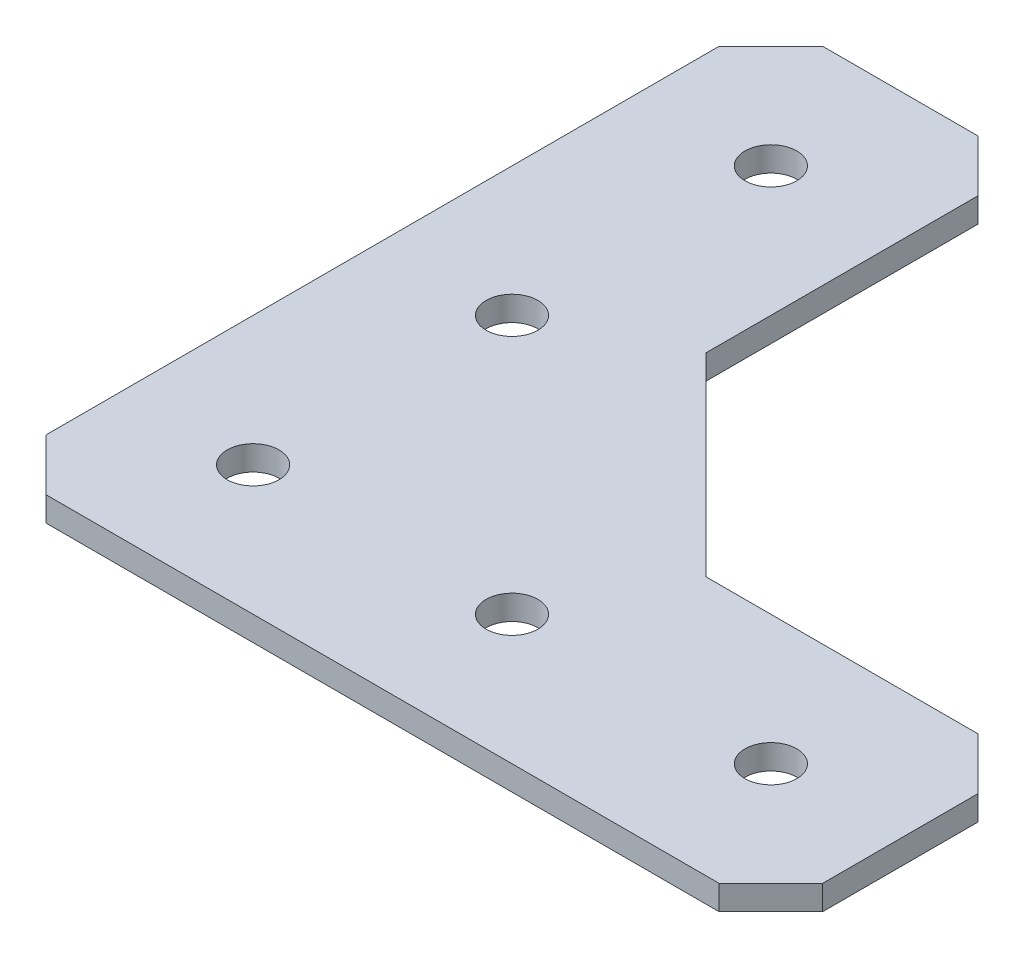
SolidWorks part; units mm, degrees
ref_plane "Front Plane" through (0, 0, 0) normal (0, 0, 1) x (1, 0, 0)
ref_plane "Top Plane" through (0, 0, 0) normal (0, 1, 0) x (1, 0, 0)
ref_plane "Right Plane" through (0, 0, 0) normal (1, 0, 0) x (0, 0, -1)
sketch "Sketch1" plane through (0, 0, 0) normal (0, 1, 0) x (1, 0, 0)
  line L0 (25.4, 76.2) -> (25.4, 25.4)
  line L1 (0, 0) -> (76.2, 0)
  line L2 (0, 0) -> (0, 76.2)
  line L3 (0, 76.2) -> (25.4, 76.2)
  line L4 (76.2, 0) -> (76.2, 25.4)
  line L5 (25.4, 25.4) -> (76.2, 25.4)
  point P1 (25.4, 23.2833)
  point P7 (25.4, 25.4)
  dimension "D1" = 25.4
  dimension "D2" = 76.2
extrude "Boss-Extrude1" add sketch "Sketch1" along normal blind 2.413
chamfer "Chamfer1" distance 19.05 angle 45 1 edges at (25.4, 1.2065, -25.4)
chamfer "Chamfer2" distance 5.08 angle 45 5 edges at (0, 1.2065, -76.2) (25.4, 1.2065, -76.2) (76.2, 1.2065, -25.4) (76.2, 1.2065, 0) (0, 1.2065, 0)
sketch "Sketch2" plane through (0, 0, 0) normal (0, 1, 0) x (1, 0, 0)
  line L0 (12.7, 76.2) -> (12.7, 0) construction
  line L1 (20.32, 76.2) -> (5.08, 76.2) construction
  line L2 (5.08, 0) -> (71.12, 0) construction
  line L3 (76.2, 12.7) -> (0, 12.7) construction
  line L4 (76.2, 5.08) -> (76.2, 20.32) construction
  line L5 (0, 71.12) -> (0, 5.08) construction
  circle A0 centre (12.7, 12.7) radius 2.54
  circle A1 centre (12.7, 38.1) radius 2.54
  circle A2 centre (38.1, 12.7) radius 2.54
  circle A3 centre (12.7, 63.5) radius 2.54
  circle A4 centre (63.5, 12.7) radius 2.54
  dimension "D1" = 5.08
  dimension "D2" = 25.4
  dimension "D3" = 25.4
  dimension "D4" = 25.4
  dimension "D5" = 25.4
extrude "Cut-Extrude1" cut sketch "Sketch2" against normal through all both and the other way through all
